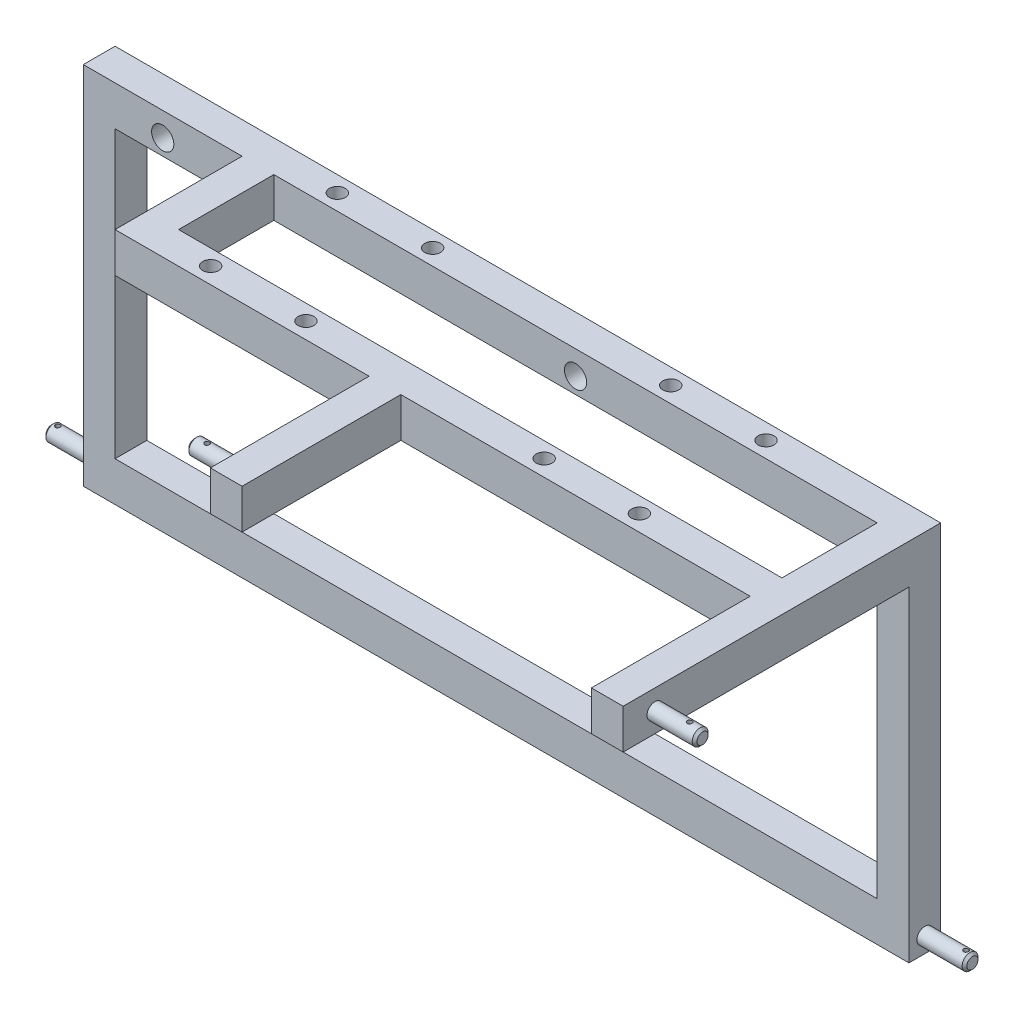
SolidWorks part; units mm, degrees
ref_plane "Ön Düzlem" through (0, 0, 0) normal (0, 0, 1) x (1, 0, 0)
ref_plane "Üst Düzlem" through (0, 0, 0) normal (0, 1, 0) x (1, 0, 0)
ref_plane "Sağ Düzlem" through (0, 0, 0) normal (1, 0, 0) x (0, 0, -1)
sketch "Çizim1" plane through (0, 0, 0) normal (0, 0, 1) x (1, 0, 0)
  line L1 (0, 0) -> (260, 0)
  line L2 (0, 0) -> (0, 115)
  line L3 (0, 115) -> (260, 115)
  line L4 (260, 0) -> (260, 115)
  line L5 (10, 12.5) -> (250, 12.5)
  line L6 (10, 12.5) -> (10, 102.5)
  line L7 (10, 102.5) -> (250, 102.5)
  line L8 (250, 12.5) -> (250, 102.5)
  dimension "D1" = 115
  dimension "D2" = 260
  dimension "D3" = 90
  dimension "D4" = 12.5
  dimension "D5" = 10
  dimension "D6" = 240
  dimension "D7" = 10
extrude "Yükseklik-Ekstrüzyon1" add sketch "Çizim1" along normal blind 10
sketch "Çizim2" plane through (0, 115, 0) normal (0, 1, 0) x (1, 0, 0)
  line L0 (260, -10) -> (260, -50)
  line L1 (260, -50) -> (50, -50)
  line L2 (50, -50) -> (50, -10)
  line L3 (260, -10) -> (0, -10) construction
  line L4 (50, -10) -> (60, -10)
  line L5 (60, -10) -> (60, -40)
  line L6 (60, -40) -> (250, -40)
  line L7 (250, -40) -> (250, -10)
  line L8 (250, -10) -> (260, -10)
  line L9 (260, 0) -> (0, 0) construction
  dimension "D1" = 210
  dimension "D2" = 50
  dimension "D3" = 30
  dimension "D4" = 190
  dimension "D5" = 10
  dimension "D6" = 10
extrude "Yükseklik-Ekstrüzyon2" add sketch "Çizim2" against normal up to vertex
sketch "Çizim3" plane through (0, 0, 50) normal (0, 0, 1) x (1, 0, 0)
  line L0 (50, 115) -> (260, 115) construction
  line L1 (260, 115) -> (250, 115)
  line L2 (260, 115) -> (260, 102.5)
  line L3 (260, 102.5) -> (250, 102.5)
  line L4 (250, 115) -> (250, 102.5)
  line L5 (130, 115) -> (140, 115)
  line L6 (130, 115) -> (130, 102.5)
  line L7 (130, 102.5) -> (140, 102.5)
  line L8 (140, 115) -> (140, 102.5)
  line L9 (50, 102.5) -> (260, 102.5) construction
  dimension "D1" = 10
  dimension "D2" = 110
extrude "Yükseklik-Ekstrüzyon3" add sketch "Çizim3" along normal blind 50
sketch "Çizim4" plane through (260, 0, 0) normal (1, 0, 0) x (0, 0, -1)
  line L0 (-100, 102.5) -> (-100, 115) construction
  line L1 (-100, 102.5) -> (-10, 102.5) construction
  circle A0 centre (-90, 108.75) radius 2.5
  dimension "D2" = 5
  dimension "D1" = 10
  dimension "D3" = 6.25
extrude "Yükseklik-Ekstrüzyon4" add sketch "Çizim4" along normal blind 15
sketch "Çizim5" plane through (0, 115, 0) normal (0, 1, 0) x (1, 0, 0)
  line L0 (275, -92.5) -> (275, -87.5) construction
  circle A0 centre (271, -90) radius 0.75
  dimension "D2" = 1.5
  dimension "D1" = 4
extrude "Kes-Ekstrüzyon1" cut sketch "Çizim5" against normal blind 15
ref_plane "Düzlem1" through (195, 0, 0) normal (1, 0, 0) x (0, 0, -1)
mirror "Aynalama1" about plane through (195, 0, 0) normal (1, 0, 0) of "Kes-Ekstrüzyon1", "Yükseklik-Ekstrüzyon4"
chamfer "Pah1" distance 0.75 angle 45 2 edges at (275, 108.75, 87.5) (115, 108.75, 87.5)
sketch "Çizim6" plane through (260, 0, 0) normal (1, 0, 0) x (0, 0, -1)
  line L0 (-10, 0) -> (0, 0) construction
  line L2 (-10, 0) -> (-10, 102.5) construction
  circle A0 centre (-5, 5) radius 2.5
  point P6 (-10, 6.5746)
  dimension "D1" = 5
  dimension "D2" = 5
  dimension "D3" = 5
extrude "Yükseklik-Ekstrüzyon5" add sketch "Çizim6" along normal blind 15
sketch "Çizim7" plane through (0, 0, 0) normal (0, -1, 0) x (1, 0, 0)
  line L0 (275, 2.5) -> (275, 7.5) construction
  line L1 (275, 7.5) -> (260, 7.5) construction
  circle A0 centre (273, 5) radius 0.75
  dimension "D1" = 1.5
  dimension "D2" = 2
  dimension "D3" = 2.5
extrude "Kes-Ekstrüzyon2" cut sketch "Çizim7" against normal blind 15
chamfer "Pah2" distance 0.75 angle 45 1 edges at (275, 5, 2.5)
ref_plane "Düzlem2" through (130, 0, 0) normal (1, 0, 0) x (0, 0, -1)
mirror "Aynalama5" about plane through (130, 0, 0) normal (1, 0, 0) of "Yükseklik-Ekstrüzyon5", "Kes-Ekstrüzyon2"
chamfer "Pah3" distance 0.75 angle 45 1 edges at (-15, 5, 2.5)
sketch "Çizim8" plane through (0, 115, 0) normal (0, 1, 0) x (1, 0, 0)
  line L0 (250, -10) -> (60, -10) construction
  line L1 (260, -100) -> (260, 0) construction
  circle A0 centre (210, -5) radius 2.5
  circle A1 centre (180, -5) radius 2.5
  circle A2 centre (105, -5) radius 2.5
  circle A3 centre (75, -5) radius 2.5
  circle A4 centre (75, -44.885) radius 2.5
  circle A5 centre (105, -44.885) radius 2.5
  circle A6 centre (180, -44.885) radius 2.5
  circle A7 centre (210, -44.885) radius 2.5
  point P16 (0, 0)
  point P21 (0, 0)
  point P22 (0, 0)
  point P23 (0, 0)
  point P24 (0, 0)
  point P25 (0, 0)
  point P26 (0, 0)
  point P27 (0, 0)
  point P28 (0, 0)
  point P29 (0, 0)
  point P30 (0, 0)
  point P31 (0, 0)
  point P32 (0, 0)
  point P33 (0, 0)
  point P34 (0, 0)
  point P35 (0, 0)
  point P36 (0, 0)
  point P37 (0, 0)
  point P38 (0, 0)
  point P39 (0, 0)
  point P40 (0, 0)
  point P41 (0, 0)
  point P42 (0, 0)
  point P43 (0, 0)
  point P44 (0, 0)
  point P45 (127.366, -14.8055)
  dimension "D3" = 5
  dimension "D1" = 135
  dimension "D2" = 75
  dimension "D6" = 5
  dimension "D7" = 50
  dimension "D8" = 30
extrude "Kes-Ekstrüzyon3" cut sketch "Çizim8" against normal blind 15
sketch "Çizim9" plane through (0, 0, 10) normal (0, 0, 1) x (1, 0, 0)
  line L0 (0, 115) -> (0, 0) construction
  line L2 (50, 102.5) -> (10, 102.5) construction
  circle A0 centre (155, 107.5) radius 3.5
  circle A1 centre (25, 107.5) radius 3.5
  point P8 (21.7803, 102.5)
  point P9 (0, 0)
  point P11 (-18.3781, 148.311)
  dimension "D1" = 7
  dimension "D2" = 25
  dimension "D3" = 5
  dimension "D4" = 130
extrude "Kes-Ekstrüzyon4" cut sketch "Çizim9" against normal blind 15
